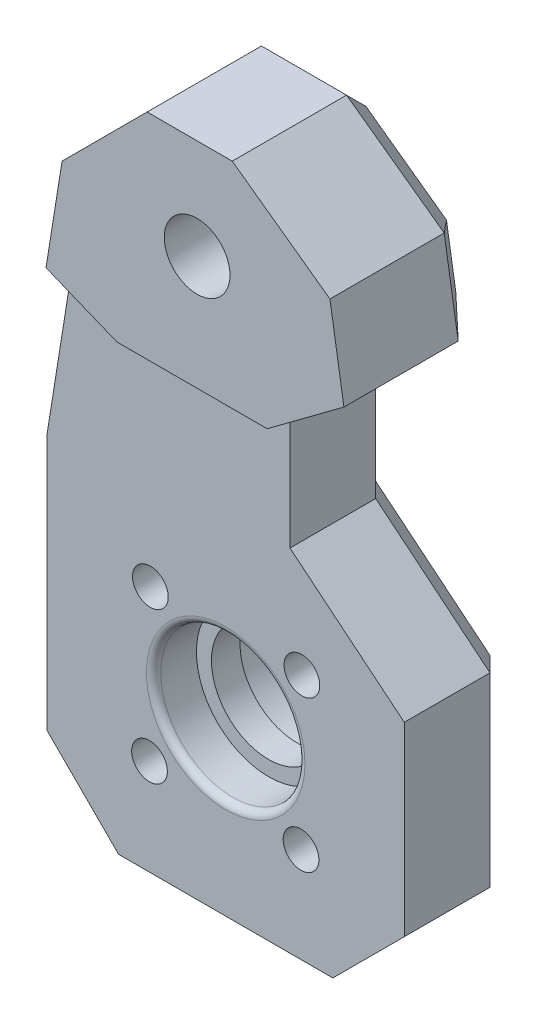
SolidWorks part; units mm, degrees
ref_plane "前视基准面" through (0, 0, 0) normal (0, 0, 1) x (1, 0, 0)
ref_plane "上视基准面" through (0, 0, 0) normal (0, 1, 0) x (1, 0, 0)
ref_plane "右视基准面" through (0, 0, 0) normal (1, 0, 0) x (0, 0, -1)
other "Configuration Table"
sketch "草图1" plane through (0, 0, 0) normal (0, 0, 1) x (1, 0, 0)
  line L0 (8.5, 36) -> (12.5, 11.2169)
  line L2 (-12.5, -12) -> (-12.5, 11)
  line L3 (-8.5, 36) -> (8.5, 36)
  line L4 (12.5, -12) -> (12.5, 11.2169)
  line L5 (0, 42.7051) -> (0, -28.0793) construction
  line L6 (-8.5, 36) -> (-12.5, 11)
  line L7 (-12.5, -12) -> (12.5, -12)
  circle A0 centre (0, 0) radius 7.5 construction
  circle A1 centre (-5.2734, 5.333) radius 1.25
  circle A2 centre (5.333, 5.2734) radius 1.25
  circle A3 centre (5.2734, -5.333) radius 1.25
  circle A4 centre (-5.333, -5.2734) radius 1.25
  circle A5 centre (0, 0) radius 4
  circle A6 centre (0, 29) radius 2.3
  point P0 (0, 0)
  point P19 (0, 0)
  dimension "D3" = 15
  dimension "D4" = 2.5
  dimension "D6" = 8
  dimension "D7" = 29
  dimension "D13" = 4.6
  dimension "D1" = 12
  dimension "D2" = 4
  dimension "D8" = 4
  dimension "D9" = 25
  dimension "D10" = 48
  dimension "D11" = 25
  dimension "D12" = 12.5
  dimension "D5" = 4
extrude "凸台-拉伸2" add sketch "草图1" along normal blind 8
chamfer "倒角1" distance 5 angle 45 2 edges at (-12.5, -12, 4) (12.5, -12, 4)
sketch "草图2" plane through (0, 0, 8) normal (0, 0, 1) x (1, 0, 0)
  line L0 (-10.5771, 23.0179) -> (-5.6138, 21)
  line L1 (-5.6138, 21) -> (5.6319, 21)
  line L2 (5.6319, 21) -> (10.5953, 23.0179)
  line L8 (12.5, 11.2169) -> (8.5, 36)
  line L9 (8.5, 36) -> (-8.5, 36)
  line L10 (-8.5, 36) -> (-12.5, 11)
  line L11 (-12.5, 11) -> (-12.5, -7)
  line L12 (-12.5, -7) -> (-7.5, -12)
  line L13 (-7.5, -12) -> (7.5, -12)
  line L14 (7.5, -12) -> (12.5, -7)
  line L15 (12.5, -7) -> (12.5, 11.2169)
  line L16 (10.5953, 23.0179) -> (8.5, 36)
  line L17 (8.5, 36) -> (-8.5, 36)
  line L18 (-8.5, 36) -> (-10.5771, 23.0179)
  dimension "D2" = 15
  dimension "D1" = 0
extrude "凸台-拉伸3" add sketch "草图2" along normal blind 2
sketch "草图3" plane through (0, 0, 8) normal (0, 0, -1) x (-1, 0, 0)
  circle A0 centre (0, 29) radius 2.3
  dimension "D1" = 4.6
extrude "切除-拉伸1" cut sketch "草图3" against normal blind 7
sketch "草图4" plane through (0, 0, 0) normal (0, 0, -1) x (-1, 0, 0)
  line L0 (-10.2754, 25) -> (-4.5, 20.7004)
  line L1 (-12.5, 11.2169) -> (-8.5, 36) construction
  line L2 (-4.5, 20.7004) -> (-4.5, 12.5658)
  line L3 (-4.5, 12.5658) -> (-12.5, 6)
  line L4 (-12.5, -7) -> (-12.5, 11.2169) construction
  line L5 (-12.5, 6) -> (-12.5, 11.2169)
  line L6 (-12.5, 11.2169) -> (-10.2754, 25)
  line L7 (-8.5, 36) -> (8.5, 36) construction
  line L8 (7.5, -12) -> (-7.5, -12) construction
  dimension "D1" = 11
  dimension "D2" = 18
  dimension "D3" = 8
extrude "切除-拉伸2" cut sketch "草图4" against normal blind 10
chamfer "倒角2" distance 5 angle 45 2 edges at (8.5, 36, 5) (-8.5, 36, 5)
chamfer "倒角3" distance 2 angle 45 13 edges at (-6.4762, 33.0238, 0) (-10.9762, 20.5238, 0) (-12.5, 2, 0) (-10, -9.5, 0) (0, -12, 0) (10, -9.5, 0) (12.5, -0.5, 0) (8.5, 9.2829, 0) (4.5, 16.6331, 0) (7.3877, 22.8502, 0) (9.786, 28.0319, 0) (5.8786, 33.5319, 0) (-0.5197, 36, 0)
sketch "草图5" plane through (0, 0, 0) normal (0, 0, -1) x (-1, 0, 0)
  circle A0 centre (0, 0) radius 5.05
  dimension "D1" = 10.1
extrude "切除-拉伸3" cut sketch "草图5" against normal blind 3
sketch "草图6" plane through (0, 0, 8) normal (0, 0, 1) x (1, 0, 0)
  circle A0 centre (0, 0) radius 5.05
  dimension "D1" = 10.1
extrude "切除-拉伸4" cut sketch "草图6" against normal blind 3
fillet "圆角1" radius 0.5 2 edges at (5.05, 0, 8) (-5.05, 0, 0)
sketch "草图7" plane through (0, 0, 0) normal (0, 0, -1) x (-1, 0, 0)
  circle A0 centre (0, 29) radius 4.05
  dimension "D1" = 8.1
extrude "切除-拉伸5" cut sketch "草图7" against normal blind 3
fillet "圆角2" radius 0.5 1 edges at (-4.05, 29, 0)
